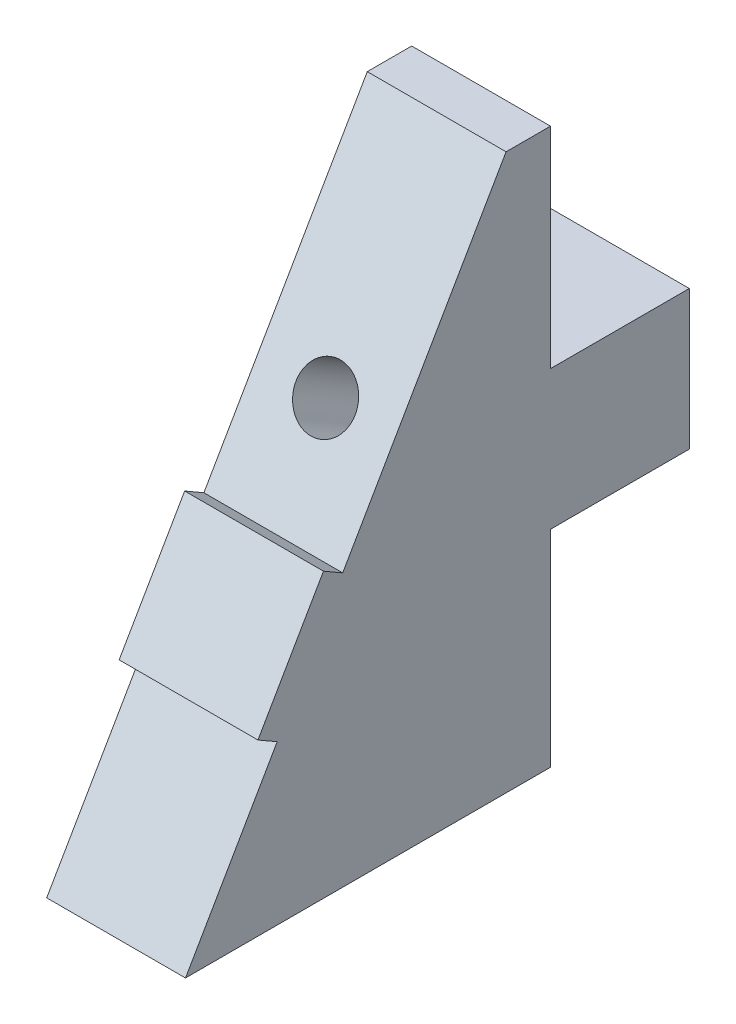
SolidWorks part; units mm, degrees
material "6061-T6 (SS)"
ref_plane "Front Plane" through (0, 0, 0) normal (0, 0, 1) x (1, 0, 0)
ref_plane "Top Plane" through (0, 0, 0) normal (0, 1, 0) x (1, 0, 0)
ref_plane "Right Plane" through (0, 0, 0) normal (1, 0, 0) x (0, 0, -1)
sketch "Sketch1" plane through (0, 0, 0) normal (1, 0, 0) x (0, 0, -1)
  line L0 (0, 0) -> (0, 25.4)
  line L1 (0, 25.4) -> (-2.032, 25.4)
  line L2 (-16.6967, 0) -> (0, 0)
  line L3 (-2.032, 25.4) -> (-16.6967, 0)
  dimension "D1" = 2.032
  dimension "D2" = 25.4
  dimension "D3" = 30
extrude "Boss-Extrude1" add sketch "Sketch1" along normal blind 6.35
sketch "Sketch2" plane through (0, 0, 0) normal (0, 0, -1) x (-1, 0, 0)
  line L1 (-6.35, 0) -> (-6.35, 25.4) construction
  line L2 (-6.35, 9.3472) -> (0, 9.3472)
  line L3 (-6.35, 9.3472) -> (-6.35, 15.875)
  line L4 (-6.35, 15.875) -> (0, 15.875)
  line L6 (0, 9.3472) -> (0, 15.875)
  line L8 (0.1778, 9.3472) -> (-6.35, 9.3472) construction
  line L9 (0, 0) -> (0, 25.4) construction
  line L10 (-6.35, 15.875) -> (0.1778, 15.875) construction
extrude "Boss-Extrude2" add sketch "Sketch2" along normal blind 6.35
sketch "Sketch8" plane through (0, 7.2299, 12.5225) normal (0, 0.5, 0.866) x (1, 0, 0)
  line L0 (0, 20.981) -> (0, -8.3483) construction
  line L1 (0, 6.122) -> (6.35, 6.122)
  line L2 (0, 6.122) -> (0, -0.0502)
  line L3 (0, -0.0502) -> (6.35, -0.0502)
  line L4 (6.35, 6.122) -> (6.35, -0.0502)
  line L5 (6.35, 20.981) -> (6.35, -8.3483) construction
  line L6 (6.35, 20.981) -> (0, 20.981) construction
  dimension "D1" = 6.1722
  dimension "D2" = 14.859
extrude "Boss-Extrude3" add sketch "Sketch8" along normal blind 1.016
hole_wizard "Tap Drill for #6-32 Tap1" positions "Sketch10" profile "Sketch9" hole size "#6-32" standard "ANSI Inch"
sketch "Sketch10" plane through (0, 7.2299, 12.5225) normal (0, 0.5, 0.866) x (1, 0, 0)
  line L0 (0, 20.981) -> (0, 6.122) construction
  line L1 (6.35, 20.981) -> (0, 20.981) construction
  point P0 (3.175, 10.821)
  dimension "D1" = 3.175
  dimension "D2" = 10.16
sketch "Sketch9" plane through (3.175, 16.6012, 7.112) normal (1, 0, 0) x (0, -0.866, 0.5)
  line L0 (0, 0) -> (0, 7.1627)
  line L1 (0, 7.1627) -> (1.3525, 6.35)
  line L2 (1.3525, 6.35) -> (1.3525, 0)
  line L5 (1.3525, 0) -> (0, 0)
  line L10 (0, 7.1627) -> (-1.3525, 6.35) construction
  line L11 (0, -6.35) -> (0, 107.95) construction
  dimension "Hole Dia." = 2.7051
  dimension "Hole Depth" = 6.35
  dimension "Drill Angle" = 118
sketch "Sketch12" plane through (0, 15.875, 0) normal (0, 1, 0) x (1, 0, 0)
  line L1 (0, 6.35) -> (6.35, 6.35)
  line L2 (0, 6.35) -> (0, 0)
  line L3 (0, 0) -> (6.35, 0)
  line L4 (6.35, 6.35) -> (6.35, 0)
extrude "Cut-Extrude2" cut sketch "Sketch12" against normal blind 0.0813
sketch "Sketch13" plane through (0, 9.3472, 0) normal (0, -1, 0) x (1, 0, 0)
  line L1 (6.35, 0) -> (0, 0)
  line L2 (6.35, 0) -> (6.35, -6.35)
  line L3 (6.35, -6.35) -> (0, -6.35)
  line L4 (0, 0) -> (0, -6.35)
extrude "Cut-Extrude3" cut sketch "Sketch13" against normal blind 0.0813
sketch "Sketch14" plane through (0, 5.3018, -3.061) normal (0, 0.866, -0.5) x (1, 0, 0)
  line L1 (0, -14.4598) -> (6.35, -14.4598)
  line L2 (0, -14.4598) -> (0, -15.4758)
  line L3 (0, -15.4758) -> (6.35, -15.4758)
  line L4 (6.35, -14.4598) -> (6.35, -15.4758)
extrude "Cut-Extrude4" cut sketch "Sketch14" against normal blind 0.0889
sketch "Sketch15" plane through (0, -0.0434, 0.0251) normal (0, -0.866, 0.5) x (1, 0, 0)
  line L1 (0, 15.4758) -> (6.35, 15.4758)
  line L2 (0, 15.4758) -> (0, 14.4598)
  line L3 (0, 14.4598) -> (6.35, 14.4598)
  line L4 (6.35, 15.4758) -> (6.35, 14.4598)
extrude "Cut-Extrude5" cut sketch "Sketch15" against normal blind 0.0889
